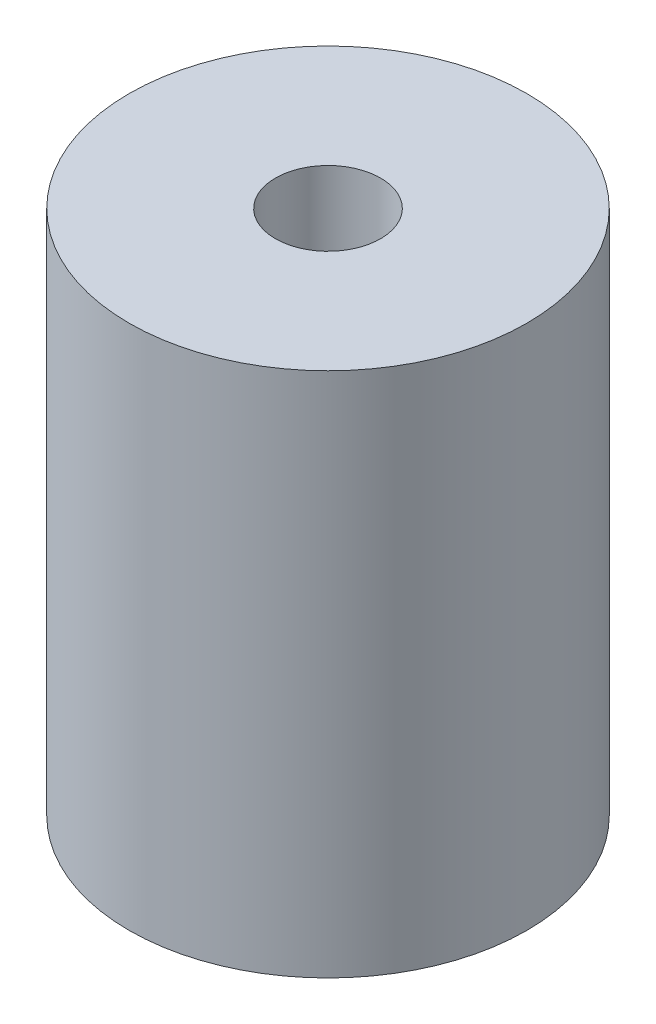
SolidWorks part; units mm, degrees
ref_plane "Front Plane" through (0, 0, 0) normal (0, 0, 1) x (1, 0, 0)
ref_plane "Top Plane" through (0, 0, 0) normal (0, 1, 0) x (1, 0, 0)
ref_plane "Right Plane" through (0, 0, 0) normal (1, 0, 0) x (0, 0, -1)
sketch "Sketch1" plane through (0, 0, 0) normal (0, 1, 0) x (1, 0, 0)
  circle A0 centre (0, 0) radius 9.455
  circle A1 centre (0, 0) radius 2.5
  dimension "D1" = 5
  dimension "D2" = 18.91
extrude "Boss-Extrude1" add sketch "Sketch1" along normal blind 25
sketch "Sketch2" plane through (0, 25, 0) normal (0, 1, 0) x (1, 0, 0)
  circle A0 centre (0, 0) radius 2.5
  circle A1 centre (0, 0) radius 2.5 construction
extrude "Boss-Extrude2" add sketch "Sketch2" against normal offset from surface (11 mm away) 7 from offset 7 up to face at (0, 0, 9.455)
